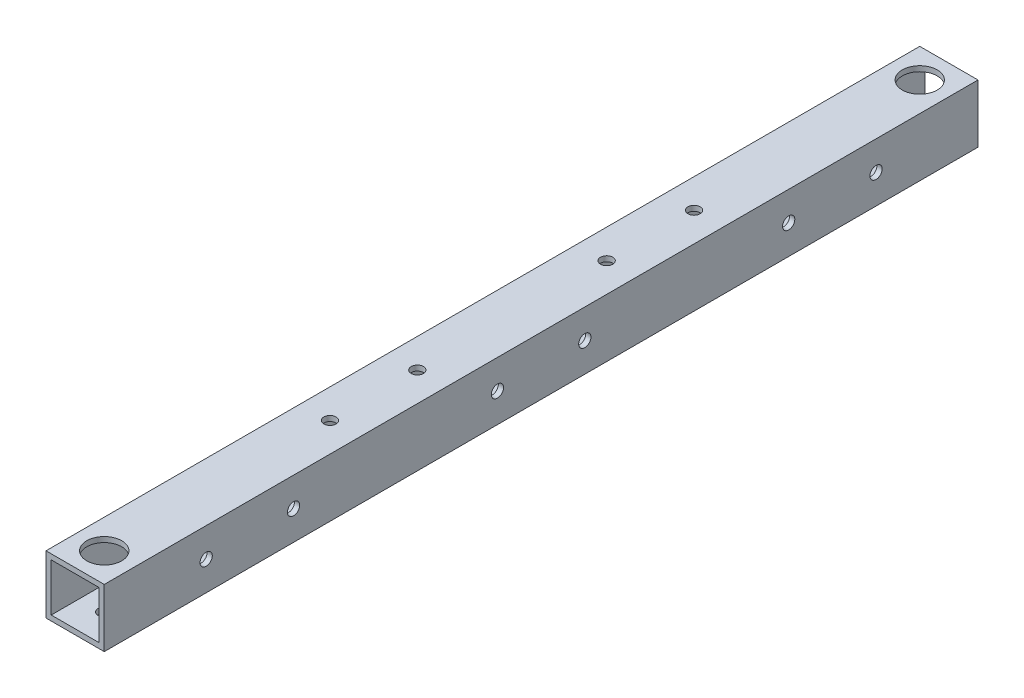
SolidWorks part; units mm, degrees
material "6061-T6 (SS)"
ref_plane "前视基准面" through (0, 0, 0) normal (0, 0, 1) x (1, 0, 0)
ref_plane "上视基准面" through (0, 0, 0) normal (0, 1, 0) x (1, 0, 0)
ref_plane "右视基准面" through (0, 0, 0) normal (1, 0, 0) x (0, 0, -1)
sketch "草图1" plane through (0, 0, 0) normal (0, 0, 1) x (1, 0, 0)
  line L1 (0, 0) -> (20, 0)
  line L2 (0, 0) -> (0, 20)
  line L6 (0, 20) -> (20, 20)
  line L7 (20, 20) -> (20, 0)
  line L8 (1.8, 1.8) -> (18.2, 1.8)
  line L9 (18.2, 18.2) -> (18.2, 1.8)
  line L10 (1.8, 18.2) -> (18.2, 18.2)
  line L11 (1.8, 1.8) -> (1.8, 18.2)
  dimension "A" = 20
  dimension "B" = 20
  dimension "T" = 1.8
sketch "草图2" plane through (0, 0, 0) normal (1, 0, 0) x (0, 0, -1)
  line L0 (0, 0) -> (300, 0) construction
  dimension "L" = 300
sketch "草图3" plane through (0, 0, 0) normal (0, 0, 1) x (1, 0, 0)
  line L0 (1.8, 1.8) -> (18.2, 1.8) construction
  line L1 (18.2, 18.2) -> (18.2, 1.8) construction
  line L2 (1.8, 18.2) -> (18.2, 18.2) construction
  line L3 (1.8, 1.8) -> (1.8, 18.2) construction
  line L10 (0, 0) -> (20, 0) construction
  line L11 (20, 20) -> (20, 0) construction
  line L12 (0, 20) -> (20, 20) construction
  line L13 (0, 0) -> (0, 20) construction
  line L14 (1.8, 1.8) -> (18.2, 1.8)
  line L15 (18.2, 18.2) -> (18.2, 1.8)
  line L16 (1.8, 18.2) -> (18.2, 18.2)
  line L17 (1.8, 1.8) -> (1.8, 18.2)
  line L18 (0, 0) -> (20, 0)
  line L19 (20, 20) -> (20, 0)
  line L20 (0, 20) -> (20, 20)
  line L21 (0, 0) -> (0, 20)
extrude "凸台-拉伸1" add sketch "草图3" against normal up to vertex (300 mm away) up to point (0, 0, -300)
sketch "草图4" plane through (0, 20, 0) normal (0, 1, 0) x (1, 0, 0)
  line L0 (0, 150) -> (20, 150) construction
  line L1 (0, 300) -> (0, 0) construction
  line L2 (20, 300) -> (20, 0) construction
  point P6 (10, 182.5)
  point P8 (10, 212.5)
  dimension "D1" = 32.5
  dimension "D2" = 10
  dimension "D4" = 30
  dimension "D3" = 2
ref_plane "基准面1" through (0, 0, -150) normal (0, 0, 1) x (1, 0, 0)
hole_wizard "Ø4.2 (4.2) 直径孔1" positions "3D草图1" profile "草图5" hole size "Ø4.2" standard "GB" end condition through all
sketch3d "3D草图1"
  point P0 (10, 20, -182.5)
  point P3 (10, 20, -212.5)
sketch "草图5" plane through (10, 20, -182.5) normal (1, 0, 0) x (0, 0, 1)
  line L0 (0, 0) -> (0, 20)
  line L1 (0, 20) -> (2.1, 20)
  line L2 (2.1, 20) -> (2.1, 0)
  line L5 (2.1, 0) -> (0, 0)
  line L11 (0, -6.35) -> (0, 107.95) construction
  dimension "通孔孔直径" = 4.2
  dimension "通孔孔深度" = 20
mirror "镜向1" about plane through (0, 0, -150) normal (0, 0, 1) of "Ø4.2 (4.2) 直径孔1"
sketch "草图6" plane through (0, 0, 0) normal (-1, 0, 0) x (0, 0, 1)
  line L0 (-300, 0) -> (0, 0) construction
  line L1 (0, 20) -> (0, 0) construction
  point P0 (-35, 10)
  point P7 (-65, 10)
  dimension "D1" = 10
  dimension "D2" = 35
  dimension "D4" = 30
  dimension "D3" = 2
hole_wizard "Ø4.2 (4.2) 直径孔2" positions "3D草图2" profile "草图7" hole size "Ø4.2" standard "GB" end condition through all
sketch3d "3D草图2"
  point P0 (0, 10, -35)
  point P3 (0, 10, -65)
sketch "草图7" plane through (0, 10, -35) normal (0, 1, 0) x (0, 0, 1)
  line L0 (0, 0) -> (0, 20)
  line L1 (0, 20) -> (2.1, 20)
  line L2 (2.1, 20) -> (2.1, 0)
  line L5 (2.1, 0) -> (0, 0)
  line L11 (0, -6.35) -> (0, 107.95) construction
  dimension "通孔孔直径" = 4.2
  dimension "通孔孔深度" = 20
mirror "镜向2" about plane through (0, 0, -150) normal (0, 0, 1) of "Ø4.2 (4.2) 直径孔2"
sketch "草图8" plane through (0, 0, 0) normal (-1, 0, 0) x (0, 0, 1)
  line L0 (-300, 0) -> (0, 0) construction
  line L1 (-150, -11) -> (-150, 11) construction
  point P0 (-165, 10)
  point P5 (-135, 10)
  dimension "D1" = 10
  dimension "D2" = 15
hole_wizard "Ø4.2 (4.2) 直径孔3" positions "3D草图3" profile "草图9" hole size "Ø4.2" standard "GB" end condition through all
sketch3d "3D草图3"
  point P0 (0, 10, -165)
  point P3 (0, 10, -135)
sketch "草图9" plane through (0, 10, -165) normal (0, 1, 0) x (0, 0, 1)
  line L0 (0, 0) -> (0, 20)
  line L1 (0, 20) -> (2.1, 20)
  line L2 (2.1, 20) -> (2.1, 0)
  line L5 (2.1, 0) -> (0, 0)
  line L11 (0, -6.35) -> (0, 107.95) construction
  dimension "通孔孔直径" = 4.2
  dimension "通孔孔深度" = 20
sketch "草图10" plane through (0, 20, 0) normal (0, 1, 0) x (1, 0, 0)
  line L0 (20, 300) -> (20, 0) construction
  line L1 (20, 0) -> (0, 0) construction
  circle A0 centre (10, 10) radius 6
  dimension "D1" = 12
  dimension "D2" = 10
  dimension "D3" = 10
extrude "切除-拉伸1" cut sketch "草图10" against normal up to next
mirror "镜向3" about plane through (0, 0, -150) normal (0, 0, 1) of "切除-拉伸1"
sketch "草图11" plane through (0, 0, 0) normal (0, -1, 0) x (1, 0, 0)
  line L0 (20, -300) -> (20, 0) construction
  line L1 (0, 0) -> (20, 0) construction
  line L2 (11, -150) -> (-11, -150) construction
  point P0 (10, -10)
  point P7 (10, -290)
  dimension "D1" = 10
  dimension "D2" = 10
hole_wizard "Ø4.2 (4.2) 直径孔4" positions "3D草图4" profile "草图12" hole size "Ø4.2" standard "GB" end condition through all
sketch3d "3D草图4"
  point P0 (10, 0, -10)
  point P3 (10, 0, -290)
sketch "草图12" plane through (10, 0, -10) normal (1, 0, 0) x (0, 0, -1)
  line L0 (0, 0) -> (0, 20)
  line L1 (0, 20) -> (2.1, 20)
  line L2 (2.1, 20) -> (2.1, 0)
  line L5 (2.1, 0) -> (0, 0)
  line L11 (0, -6.35) -> (0, 107.95) construction
  dimension "通孔孔直径" = 4.2
  dimension "通孔孔深度" = 20
